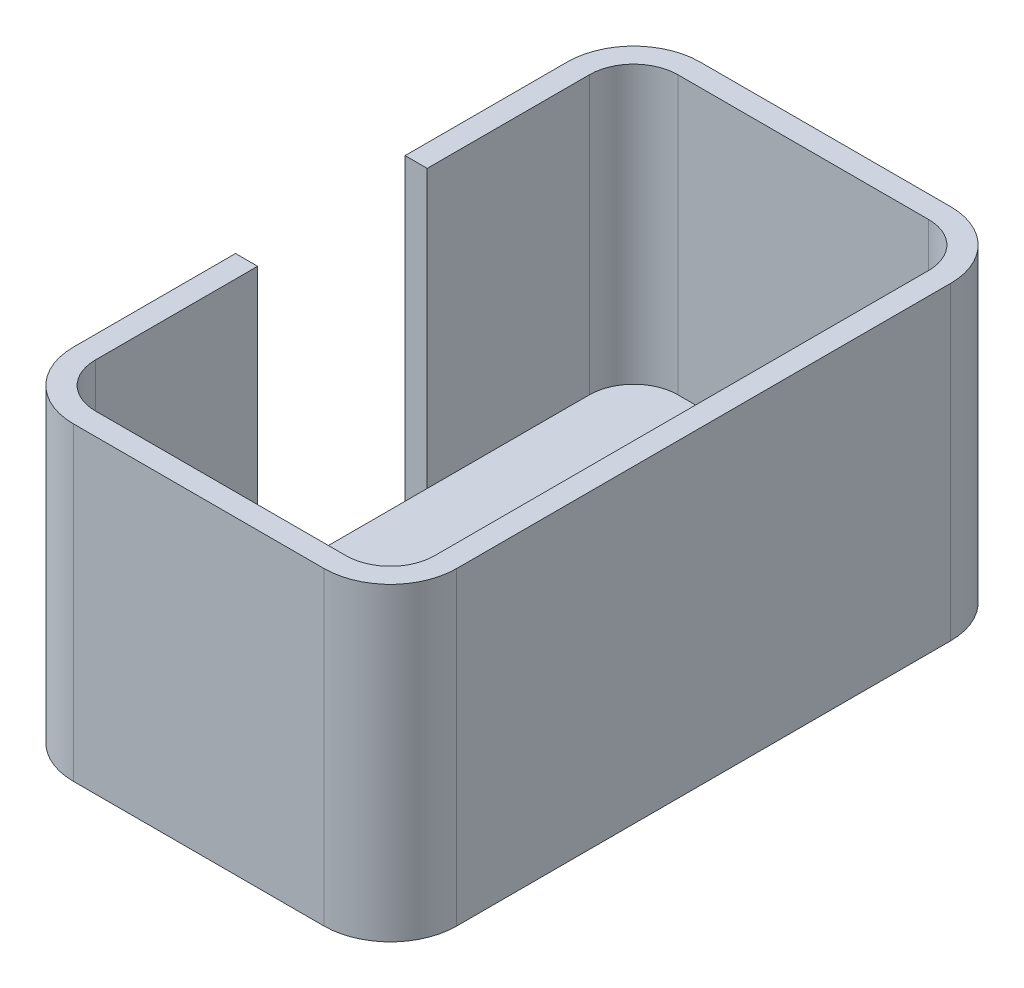
SolidWorks part; units mm, degrees
ref_plane "前视基准面" through (0, 0, 0) normal (0, 0, 1) x (1, 0, 0)
ref_plane "上视基准面" through (0, 0, 0) normal (0, 1, 0) x (1, 0, 0)
ref_plane "右视基准面" through (0, 0, 0) normal (1, 0, 0) x (0, 0, -1)
other "Configuration Table"
sketch "草图2" plane through (0, 0, 0) normal (0, 1, 0) x (1, 0, 0)
  line L0 (0, 0) -> (-11.5, 0) construction
  line L1 (-8.5, -19.75) -> (8.5, -19.75)
  line L3 (-8.5, 19.75) -> (8.5, 19.75)
  line L4 (11.5, -16.75) -> (11.5, 16.75)
  line L5 (-11.5, -19.75) -> (11.5, 19.75) construction
  line L6 (-11.5, 19.75) -> (11.5, -19.75) construction
  line L7 (-11.5, 0) -> (-11.5, 5.75) construction
  line L8 (-11.5, 0) -> (-11.5, -5.75) construction
  line L9 (-11.5, 16.75) -> (-11.5, 5.75)
  line L10 (-11.5, -5.75) -> (-11.5, -16.75)
  arc A0 (-8.5, -19.75) -> (-11.5, -16.75) centre (-8.5, -16.75) cw
  arc A1 (8.5, -19.75) -> (11.5, -16.75) centre (8.5, -16.75) ccw
  arc A2 (-11.5, 16.75) -> (-8.5, 19.75) centre (-8.5, 16.75) cw
  arc A3 (8.5, 19.75) -> (11.5, 16.75) centre (8.5, 16.75) cw
  point P0 (0, 0)
  dimension "D4" = 3
  dimension "D1" = 23
  dimension "D2" = 39.5
  dimension "D3" = 11.5
extrude "拉伸-薄壁1" add sketch "草图2" along normal blind 21 thin
sketch "草图3" plane through (0, 0, 0) normal (0, 1, 0) x (1, 0, 0)
  line L0 (0, 0) -> (-11.5, 0) construction
  line L1 (-8.5, -19.75) -> (8.5, -19.75)
  line L3 (-8.5, 19.75) -> (8.5, 19.75)
  line L4 (11.5, -16.75) -> (11.5, 16.75)
  line L5 (-11.5, -19.75) -> (11.5, 19.75) construction
  line L6 (-11.5, 19.75) -> (11.5, -19.75) construction
  line L7 (-11.5, 0) -> (-11.5, 5.75)
  line L8 (-11.5, 0) -> (-11.5, -5.75)
  line L9 (-11.5, 16.75) -> (-11.5, 5.75)
  line L10 (-11.5, -5.75) -> (-11.5, -16.75)
  arc A0 (-8.5, -19.75) -> (-11.5, -16.75) centre (-8.5, -16.75) cw
  arc A1 (8.5, -19.75) -> (11.5, -16.75) centre (8.5, -16.75) ccw
  arc A2 (-11.5, 16.75) -> (-8.5, 19.75) centre (-8.5, 16.75) cw
  arc A3 (8.5, 19.75) -> (11.5, 16.75) centre (8.5, 16.75) cw
  point P0 (0, 0)
  dimension "D4" = 3
  dimension "D1" = 23
  dimension "D2" = 39.5
  dimension "D3" = 11.5
extrude "凸台-拉伸1" add sketch "草图3" along normal blind 2.2
